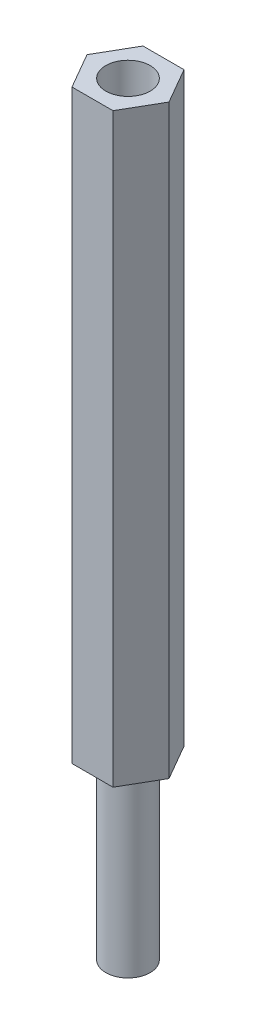
SolidWorks part; units mm, degrees
ref_plane "Front Plane" through (0, 0, 0) normal (0, 0, 1) x (1, 0, 0)
ref_plane "Top Plane" through (0, 0, 0) normal (0, 1, 0) x (1, 0, 0)
ref_plane "Right Plane" through (0, 0, 0) normal (1, 0, 0) x (0, 0, -1)
sketch "Sketch1" plane through (0, 0, 0) normal (0, 1, 0) x (1, 0, 0)
  line L0 (0, 0) -> (0, 2.0858) construction
  line L1 (1.1547, -2) -> (2.3094, 0)
  line L2 (2.3094, 0) -> (1.1547, 2)
  line L3 (1.1547, 2) -> (-1.1547, 2)
  line L4 (-1.1547, 2) -> (-2.3094, 0)
  line L5 (-2.3094, 0) -> (-1.1547, -2)
  line L6 (-1.1547, -2) -> (1.1547, -2)
  circle A0 centre (0, 0) radius 2 construction
  dimension "D1" = 4
extrude "Boss-Extrude1" add sketch "Sketch1" along normal blind 33
sketch "Sketch2" plane through (0, 0, 0) normal (0, 1, 0) x (1, 0, 0)
  circle A0 centre (0, 0) radius 1.25
  dimension "D1" = 2.5
extrude "Boss-Extrude2" add sketch "Sketch2" against normal blind 10
sketch "Sketch3" plane through (0, 33, 0) normal (0, 1, 0) x (1, 0, 0)
  circle A0 centre (0, 0) radius 1.25
  dimension "D1" = 2.5
extrude "Cut-Extrude1" cut sketch "Sketch3" against normal blind 10
